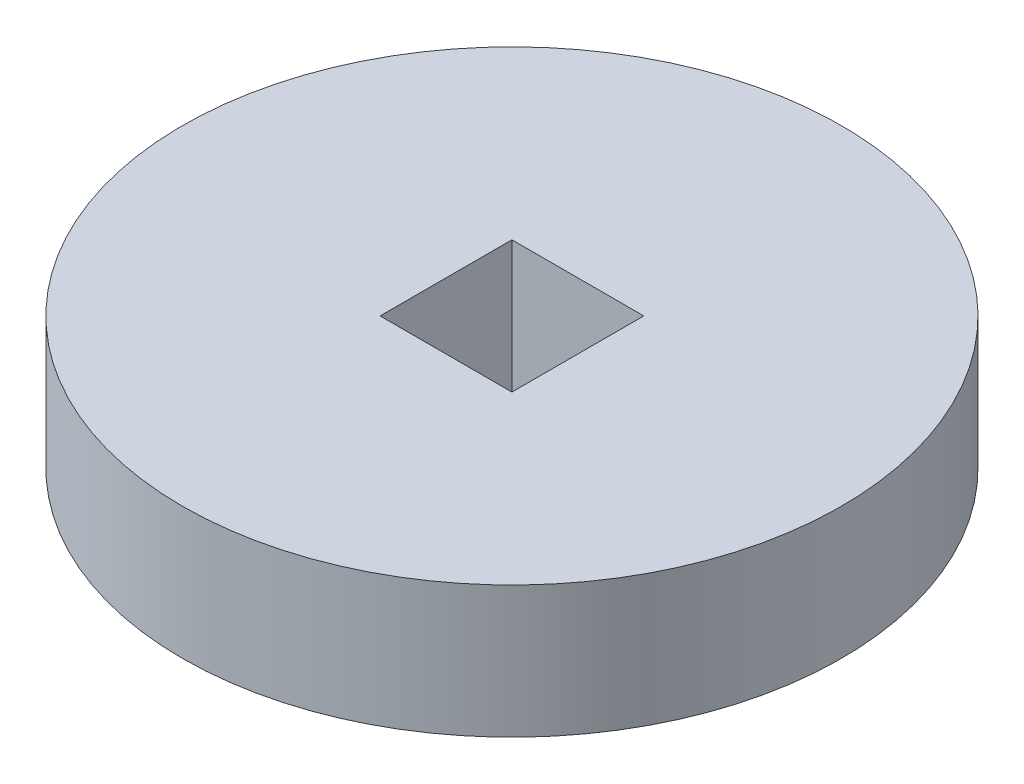
SolidWorks part; units mm, degrees
ref_plane "Front Plane" through (0, 0, 0) normal (0, 0, 1) x (1, 0, 0)
ref_plane "Top Plane" through (0, 0, 0) normal (0, 1, 0) x (1, 0, 0)
ref_plane "Right Plane" through (0, 0, 0) normal (1, 0, 0) x (0, 0, -1)
sketch "Elevator Support Pulleys" plane through (0, 0, 0) normal (0, 1, 0) x (1, 0, 0)
  line L1 (-3.175, 3.175) -> (3.175, 3.175)
  line L2 (-3.175, 3.175) -> (-3.175, -3.175)
  line L3 (-3.175, -3.175) -> (3.175, -3.175)
  line L4 (3.175, 3.175) -> (3.175, -3.175)
  line L5 (-3.175, 3.175) -> (3.175, -3.175) construction
  line L6 (-3.175, -3.175) -> (3.175, 3.175) construction
  circle A0 centre (0, 0) radius 15.875
  dimension "D1" = 31.75
  dimension "D2" = 6.35
  dimension "D3" = 6.35
extrude "Boss-Extrude1" add sketch "Elevator Support Pulleys" along normal blind 6.35
equation "\"Ball Diameter\"= 1.75in"
equation "\"Sheet Thickness\"= 0.25in"
equation "\"Screw Diameter\"= .17in"
equation "\"Robot Diameter\"= 14in"
equation "\"Castor Screw Diameter\"= 0.22in"
equation "\"Wheel Diameter\" = 4in"
equation "\"Nut Diameter\" = 8.4mm"
equation "\"Nut Height\" = 2.9mm"
equation "\"Screw Height\" = 0.55in"
equation "\"Pulley Diameter\" = 1in"
equation "\"Reactor Height\" = 14in"
equation "\"Elevator Height\" = 11.5in"
equation "\"Elevator Width\" = \"Ball Diameter\" + 0.25in"
equation "\"Elevator Axle Length\" = \"Elevator Width\" + 8*\"Sheet Thickness\""
equation "\"D1@Elevator Support Pulleys\"=\"Elevator Axle Endcap Diameter\""
equation "\"D2@Elevator Support Pulleys\"=\"Sheet Thickness\""
equation "\"D3@Elevator Support Pulleys\"=\"Sheet Thickness\""
equation "\"D1@Boss-Extrude1\"=\"Sheet Thickness\""
equation "\"Elevator Bearing Diameter\" = sqr(2*(\"Sheet Thickness\"^2)) + 0.2in"
equation "\"Elevator Axle Endcap Diameter\" = \"Pulley Diameter\" + 0.25in"
